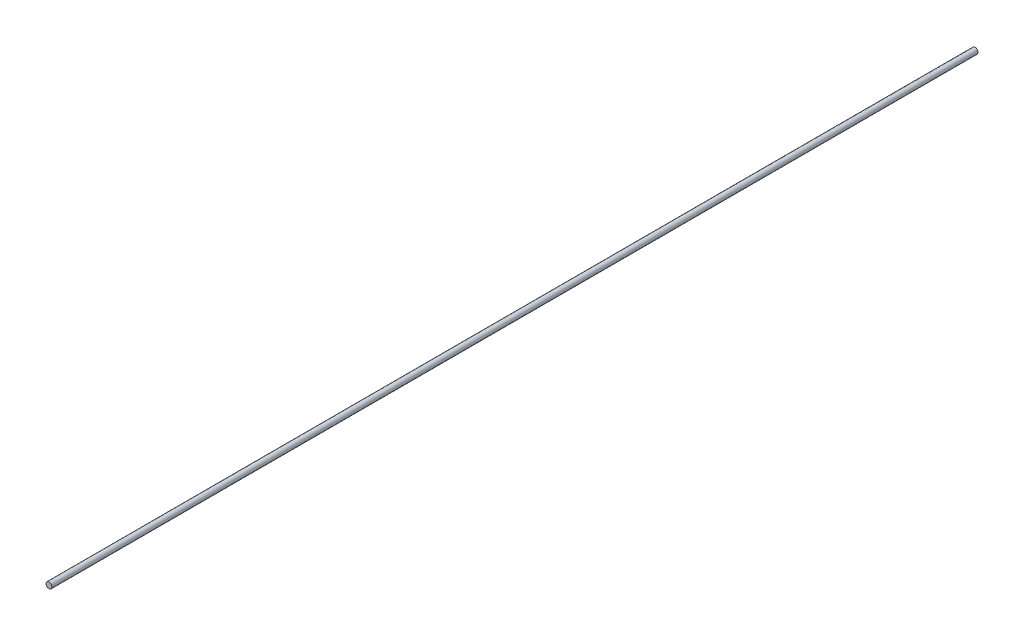
SolidWorks part; units mm, degrees
material "AISI 4340 Aço, normalizado"
ref_plane "Plano frontal" through (0, 0, 0) normal (0, 0, 1) x (1, 0, 0)
ref_plane "Plano superior" through (0, 0, 0) normal (0, 1, 0) x (1, 0, 0)
ref_plane "Plano direito" through (0, 0, 0) normal (1, 0, 0) x (0, 0, -1)
sketch "Esboço1" plane through (0, 0, 0) normal (0, 0, 1) x (1, 0, 0)
  circle A0 centre (0, 0) radius 4.7625
  dimension "D1" = 9.525
extrude "Ressalto-extrusão1" add sketch "Esboço1" along normal blind 1500
